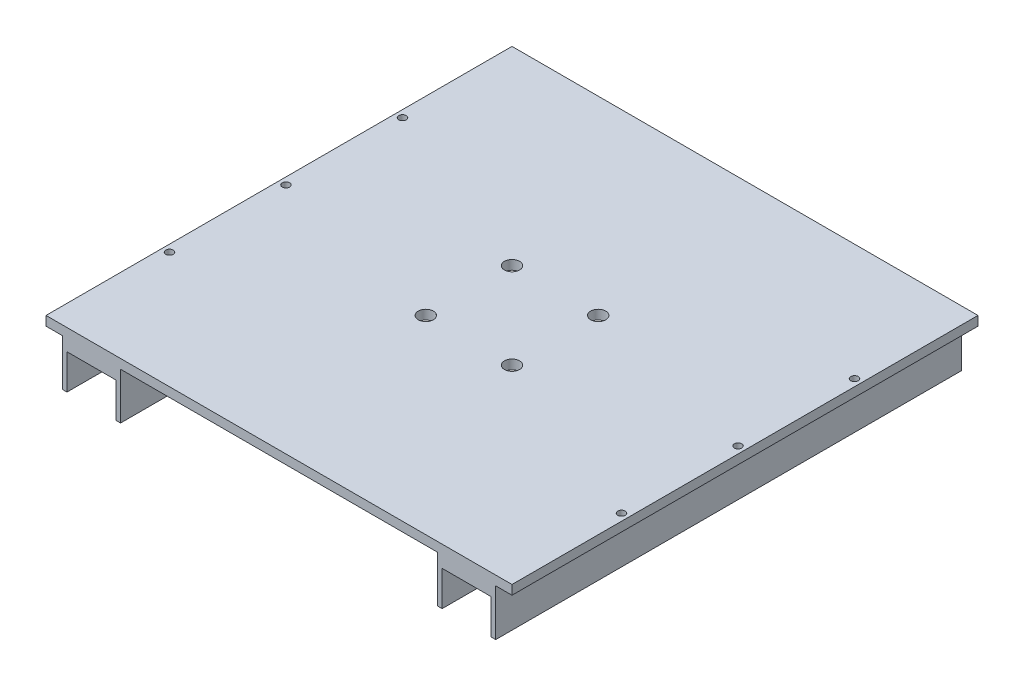
SolidWorks part; units mm, degrees
ref_plane "前视基准面" through (0, 0, 0) normal (0, 0, 1) x (1, 0, 0)
ref_plane "上视基准面" through (0, 0, 0) normal (0, 1, 0) x (1, 0, 0)
ref_plane "右视基准面" through (0, 0, 0) normal (1, 0, 0) x (0, 0, -1)
sketch "草图1" plane through (0, 0, 0) normal (0, 1, 0) x (1, 0, 0)
  line L1 (-100, 100) -> (100, 100)
  line L2 (-100, 100) -> (-100, -100)
  line L3 (-100, -100) -> (100, -100)
  line L4 (100, 100) -> (100, -100)
  line L5 (0, -100) -> (0, 100) construction
  line L6 (-100, 0) -> (100, 0) construction
  point P0 (0, 0)
  dimension "D1" = 200
  dimension "D2" = 200
extrude "凸台-拉伸1" add sketch "草图1" along normal blind 4
sketch "草图2" plane through (0, 0, 0) normal (0, -1, 0) x (1, 0, 0)
  line L0 (0, 0) -> (0, 80.4527) construction
  line L1 (-70, 100) -> (-70, -100)
  line L2 (-100, 100) -> (100, 100) construction
  line L3 (100, -100) -> (-100, -100) construction
  line L4 (-70, -100) -> (-68, -100)
  line L5 (-68, -100) -> (-68, 100)
  line L6 (-68, 100) -> (-70, 100)
  line L7 (-91, 100) -> (-91, -100)
  line L8 (-93, -100) -> (-93, 100)
  line L9 (-93, 100) -> (-91, 100)
  line L10 (-93, -100) -> (-91, -100)
  dimension "D1" = 70
  dimension "D2" = 2
  dimension "D3" = 21
  dimension "D4" = 2
extrude "凸台-拉伸2" add sketch "草图2" along normal blind 20
mirror "镜向1" about plane through (0, 0, 0) normal (1, 0, 0) of "凸台-拉伸2"
sketch "草图4" plane through (0, 4, 0) normal (0, 1, 0) x (1, 0, 0)
  line L0 (-80.5, 100) -> (-80.5, -100) construction
  line L1 (-18.5, 18.5) -> (18.5, 18.5) construction
  line L2 (-18.5, 18.5) -> (-18.5, -18.5) construction
  line L3 (-18.5, -18.5) -> (18.5, -18.5) construction
  line L4 (18.5, 18.5) -> (18.5, -18.5) construction
  line L5 (0, -18.5) -> (0, 18.5) construction
  line L6 (-18.5, 0) -> (18.5, 0) construction
  line L7 (-70, 100) -> (-91, 100) construction
  line L8 (-91, -100) -> (-70, -100) construction
  line L9 (80.5, 100) -> (80.5, -100) construction
  line L10 (91, 100) -> (70, 100) construction
  line L11 (70, -100) -> (91, -100) construction
  line L12 (97, -50) -> (100, -50) construction
  line L13 (100, -100) -> (100, 100) construction
  circle A0 centre (18.5, 18.5) radius 3.25
  circle A1 centre (18.5, -18.5) radius 3.25
  circle A2 centre (-18.5, -18.5) radius 3.25
  circle A3 centre (-18.5, 18.5) radius 3.25
  circle A8 centre (97, -50) radius 1.6
  circle A9 centre (97, 50) radius 1.6
  circle A10 centre (-97, -50) radius 1.6
  circle A11 centre (-97, 50) radius 1.6
  circle A12 centre (-97, 0) radius 1.6
  circle A13 centre (97, 0) radius 1.6
  point P0 (0, 0)
  dimension "D3" = 6.5
  dimension "D4" = 6.5
  dimension "D5" = 6.5
  dimension "D6" = 6.5
  dimension "D7" = 3.2
  dimension "D9" = 3.2
  dimension "D11" = 3.2
  dimension "D1" = 37
  dimension "D2" = 37
  dimension "D10" = 3
extrude "切除-拉伸1" cut sketch "草图4" against normal blind 10
sketch "草图5" plane through (0, 0, 0) normal (0, -1, 0) x (1, 0, 0)
  line L0 (70, 100) -> (70, 75)
  line L1 (70, 100) -> (70, -100) construction
  line L2 (70, 75) -> (91, 75)
  line L3 (91, -100) -> (91, 100) construction
  line L4 (91, 75) -> (91, 100)
  line L5 (91, 100) -> (70, 100)
  line L6 (70, -100) -> (70, -75)
  line L7 (70, -75) -> (91, -75)
  line L8 (91, -75) -> (91, -100)
  line L9 (91, -100) -> (70, -100)
  dimension "D1" = 25
  dimension "D2" = 25
extrude "凸台-拉伸3" add sketch "草图5" along normal blind 5
mirror "镜向2" about plane through (0, 0, 0) normal (1, 0, 0) of "凸台-拉伸3"
